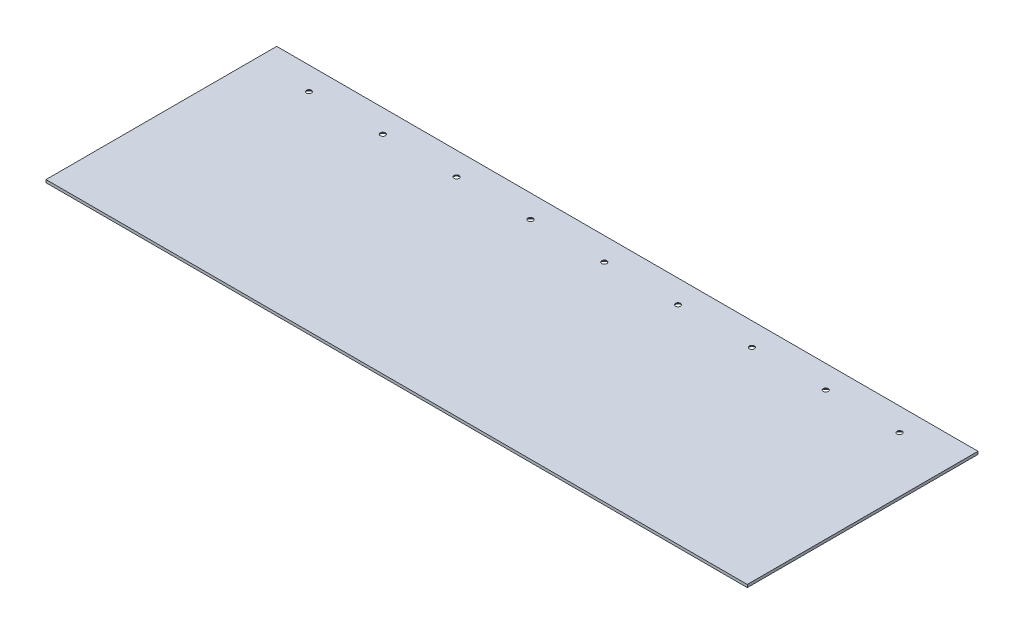
SolidWorks part; units mm, degrees
ref_plane "Front Plane" through (0, 0, 0) normal (0, 0, 1) x (1, 0, 0)
ref_plane "Top Plane" through (0, 0, 0) normal (0, 1, 0) x (1, 0, 0)
ref_plane "Right Plane" through (0, 0, 0) normal (1, 0, 0) x (0, 0, -1)
sketch "Sketch1" plane through (0, 0, 0) normal (0, 1, 0) x (1, 0, 0)
  line L1 (-380, 125) -> (380, 125)
  line L2 (-380, 125) -> (-380, -125)
  line L3 (-380, -125) -> (380, -125)
  line L4 (380, 125) -> (380, -125)
  line L5 (-380, 125) -> (380, -125) construction
  line L6 (-380, -125) -> (380, 125) construction
  point P0 (0, 0)
  dimension "D1" = 760
  dimension "D2" = 250
extrude "Boss-Extrude1" add sketch "Sketch1" along normal blind 3
hole_wizard "CSK for M5 Countersunk Flat Head Screw1" positions "Sketch2" profile "Sketch3" countersink size "M5" standard "ISO" end condition through all
sketch "Sketch2" plane through (0, 0, 0) normal (0, -1, 0) x (-1, 0, 0)
  line L0 (-380, 125) -> (380, 125) construction
  point P0 (0, 100)
  point P13 (80, 100)
  point P14 (160, 100)
  point P15 (240, 100)
  point P16 (320, 100)
  point P23 (-80, 100)
  point P24 (-160, 100)
  point P25 (-240, 100)
  point P26 (-320, 100)
  dimension "D1" = 25
  dimension "D2" = 5
  dimension "D3" = 5
sketch "Sketch3" plane through (0, 0, -100) normal (1, 0, 0) x (0, 0, -1)
  line L0 (0, 0) -> (0, 3)
  line L1 (0, 3) -> (2.75, 3)
  line L2 (2.75, 3) -> (2.75, 2.45)
  line L3 (2.75, 2.45) -> (5.2, 0)
  line L5 (5.2, 0) -> (0, 0)
  line L6 (-2.75, 2.45) -> (-5.2, 0) construction
  line L11 (0, -6.35) -> (0, 107.95) construction
  dimension "Thru Hole Dia." = 5.5
  dimension "Thru Hole Depth" = 3
  dimension "Near C'Sink Dia." = 10.4
  dimension "Near C'Sink Angle" = 90
